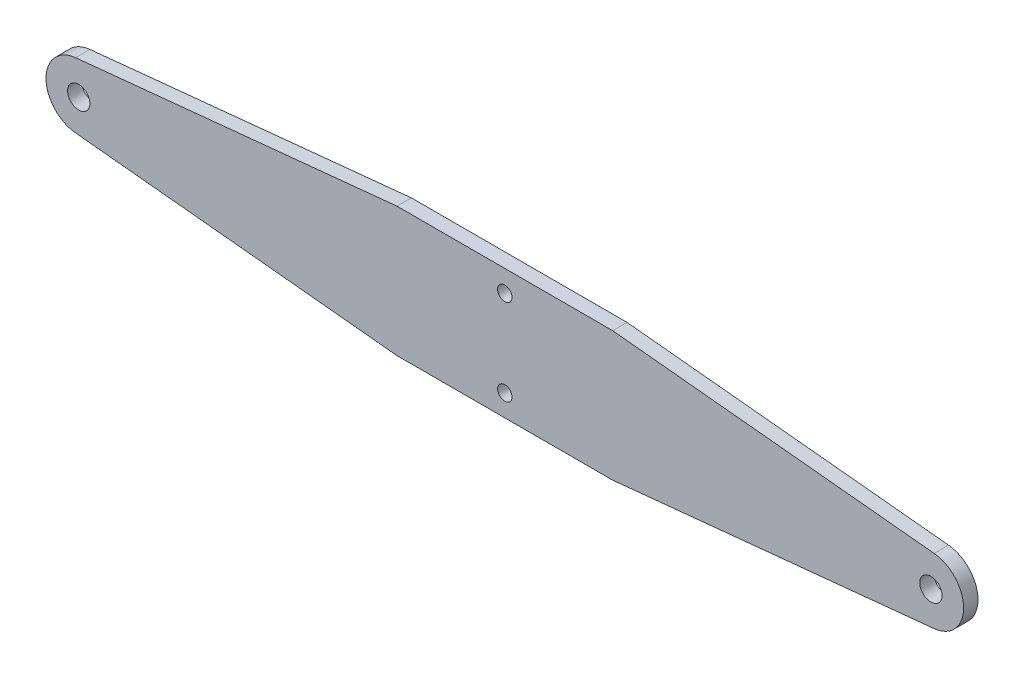
SolidWorks part; units mm, degrees
ref_plane "Front Plane" through (0, 0, 0) normal (0, 0, 1) x (1, 0, 0)
ref_plane "Top Plane" through (0, 0, 0) normal (0, 1, 0) x (1, 0, 0)
ref_plane "Right Plane" through (0, 0, 0) normal (1, 0, 0) x (0, 0, -1)
sketch "Sketch1" plane through (0, 0, 0) normal (0, 0, 1) x (1, 0, 0)
  line L0 (59.25, 0) -> (-59.25, 0) construction
  line L1 (15, -9) -> (-15, -9)
  line L3 (15, 9) -> (-15, 9)
  line L5 (0, 0) -> (-76.3496, 0) construction
  line L6 (0, -9) -> (0, 9) construction
  line L7 (-59.703, 4.5274) -> (-15, 9)
  line L8 (-59.703, -4.5274) -> (-15, -9)
  line L9 (59.703, 4.5274) -> (15, 9)
  line L10 (59.703, -4.5274) -> (15, -9)
  line L11 (0, 6) -> (0, -6) construction
  circle A0 centre (-59.25, 0) radius 1.55
  circle A1 centre (59.25, 0) radius 1.55
  arc A2 (-59.703, 4.5274) -> (-59.703, -4.5274) centre (-59.25, 0) ccw
  arc A3 (59.703, -4.5274) -> (59.703, 4.5274) centre (59.25, 0) ccw
  circle A4 centre (0, -6) radius 1
  circle A6 centre (0, 6) radius 1
  circle A7 centre (-59.25, 0) radius 1.25 construction
  circle A8 centre (-59.25, 0) radius 1.25 construction
  circle A13 centre (0, 6) radius 1.1 construction
  circle A14 centre (0, -6) radius 1.1 construction
  circle A15 centre (0, 6) radius 1.1 construction
  circle A16 centre (0, -6) radius 1.1 construction
  point P0 (0, 0)
  point P9 (0, 0)
  dimension "D2" = 3.1
  dimension "D7" = 2
  dimension "D1" = 30
  dimension "D4" = 3
  dimension "D5" = 18
  dimension "D3" = 12
  dimension "D6" = 12
extrude "Boss-Extrude1" add sketch "Sketch1" along normal blind 2
equation "\"D6@Sketch1\"=\"D3@Sketch1\""
